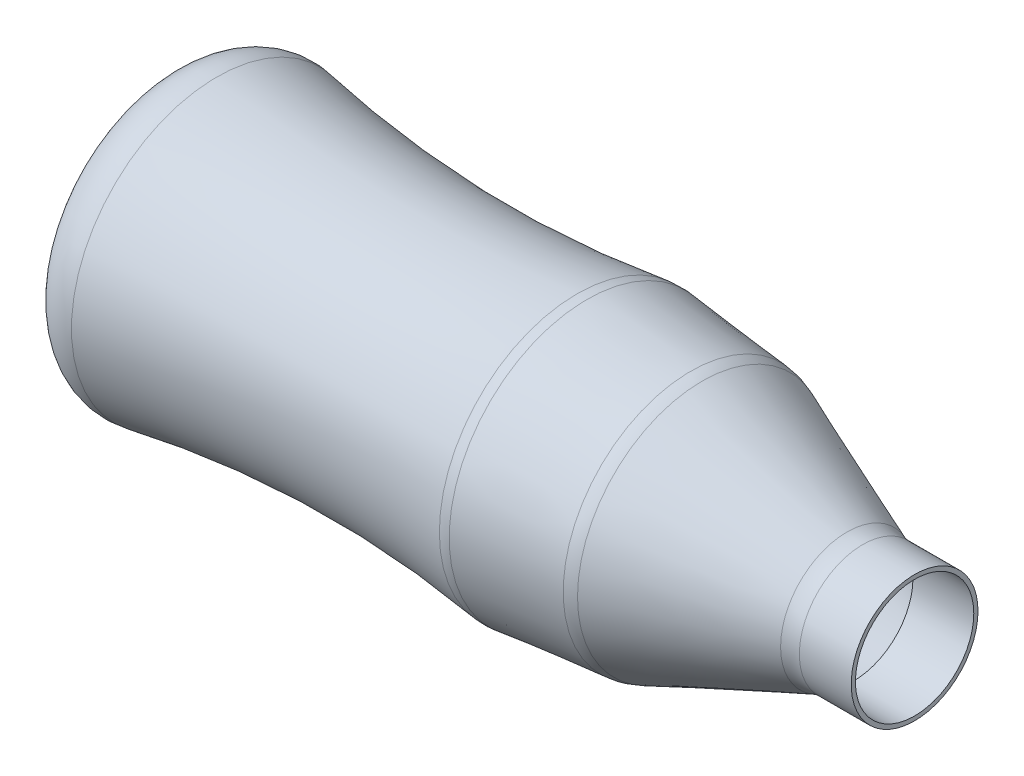
SolidWorks part; units mm, degrees
ref_plane "Front Plane" through (0, 0, 0) normal (0, 0, 1) x (1, 0, 0)
ref_plane "Top Plane" through (0, 0, 0) normal (0, 1, 0) x (1, 0, 0)
ref_plane "Right Plane" through (0, 0, 0) normal (1, 0, 0) x (0, 0, -1)
sketch "Sketch1" plane through (0, 0, 0) normal (0, 0, 1) x (1, 0, 0)
  line L0 (0, 0) -> (0, 37317.267) construction
  line L1 (0, 0) -> (-37317.267, 0) construction
  line L2 (-72.0076, 0) -> (-72.0076, 24.57)
  line L3 (-68.0903, 34.57) -> (-54.2138, 34.57)
  line L4 (-71.0076, 0) -> (-71.0076, 24.57)
  line L5 (26.1716, 31.7429) -> (53.0005, 29.0194)
  line L6 (26.1519, 32.75) -> (53.2419, 30)
  line L7 (53.2419, 30) -> (90.6319, 15)
  line L8 (90.6319, 15) -> (104.8219, 15)
  line L10 (53.0005, 29.0194) -> (90.4388, 14)
  line L11 (90.4388, 14) -> (103.8219, 14)
  line L13 (-72.0076, 0) -> (-71.0076, 0)
  line L14 (103.8219, 0) -> (104.8219, 0)
  line L15 (103.8219, 14) -> (104.8219, 14)
  line L16 (103.8219, 14) -> (103.8219, 0) construction
  line L17 (104.8219, 15) -> (104.8219, 0) construction
  line L18 (104.8219, 14) -> (104.8219, 15)
  arc A0 (-60.2281, 34.4104) -> (26.1519, 32.75) centre (-11.8834, 301.7473) ccw
  arc A1 (-72.0076, 24.57) -> (-60.2281, 34.4104) centre (-62.0076, 24.57) cw
  arc A2 (-71.0076, 24.57) -> (-60.4061, 33.4264) centre (-62.0076, 24.57) cw
  arc A3 (-60.4061, 33.4264) -> (26.1716, 31.7429) centre (-11.8834, 301.7473) ccw
  dimension "D2" = 10
  dimension "D9" = 34.57
  dimension "D1" = 30
  dimension "D3" = 27.09
  dimension "D4" = 37.39
  dimension "D5" = 14.19
  dimension "D6" = 32.75
  dimension "D7" = 15
  dimension "D8" = 86.38
  dimension "D10" = 1
revolve "Revolve2" add sketch "Sketch1" angle 360 about L1
fillet "Fillet1" radius 10 3 edges at (90.6319, 0, -15) (53.2419, 0, -30) (26.1519, 0, -32.75)
